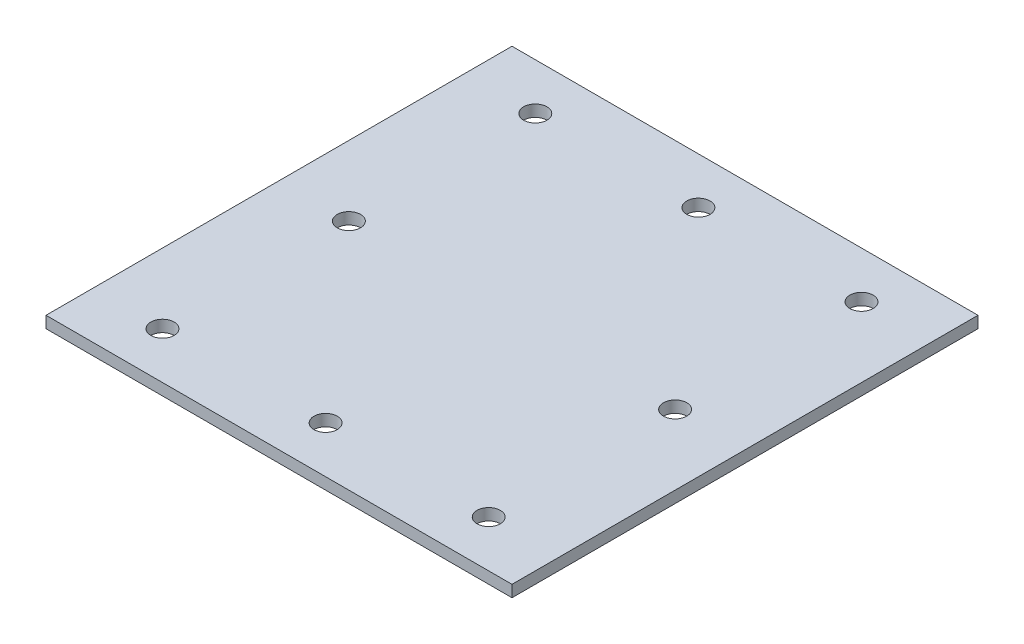
SolidWorks part; units mm, degrees
material "1060 Alloy"
ref_plane "Front Plane" through (0, 0, 0) normal (0, 0, 1) x (1, 0, 0)
ref_plane "Top Plane" through (0, 0, 0) normal (0, 1, 0) x (1, 0, 0)
ref_plane "Right Plane" through (0, 0, 0) normal (1, 0, 0) x (0, 0, -1)
sketch "Sketch1" plane through (0, 0, 0) normal (0, 1, 0) x (1, 0, 0)
  line L1 (254, 254) -> (-254, 254)
  line L2 (254, 254) -> (254, -254)
  line L3 (254, -254) -> (-254, -254)
  line L4 (-254, 254) -> (-254, -254)
  line L5 (254, 254) -> (-254, -254) construction
  line L6 (254, -254) -> (-254, 254) construction
  point P0 (0, 0)
  dimension "D1" = 508
  dimension "D2" = 508
extrude "Boss-Extrude1" add sketch "Sketch1" along normal blind 12.7
sketch "Sketch2" plane through (0, 12.7, 0) normal (0, 1, 0) x (1, 0, 0)
  line L0 (254, 254) -> (-254, 254) construction
  line L1 (-254, 254) -> (-254, -254) construction
  line L2 (-254, -254) -> (254, -254) construction
  circle A0 centre (-177.8, 203.2) radius 12.7
  circle A1 centre (0, 203.2) radius 12.7
  circle A2 centre (177.8, 203.2) radius 12.7
  circle A3 centre (-177.8, 0) radius 12.7
  circle A5 centre (177.8, 0) radius 12.7
  circle A6 centre (-177.8, -203.2) radius 12.7
  circle A7 centre (0, -203.2) radius 12.7
  circle A8 centre (177.8, -203.2) radius 12.7
  circle A9 centre (0, 0) radius 12.7 [skipped]
  dimension "D3" = 25.4
  dimension "D6" = 50.8
  dimension "D1" = 50.8
  dimension "D2" = 76.2
  dimension "D4" = 3
  dimension "D5" = 3
extrude "Cut-Extrude1" cut sketch "Sketch2" against normal through all contours A6 | A8 | A7
